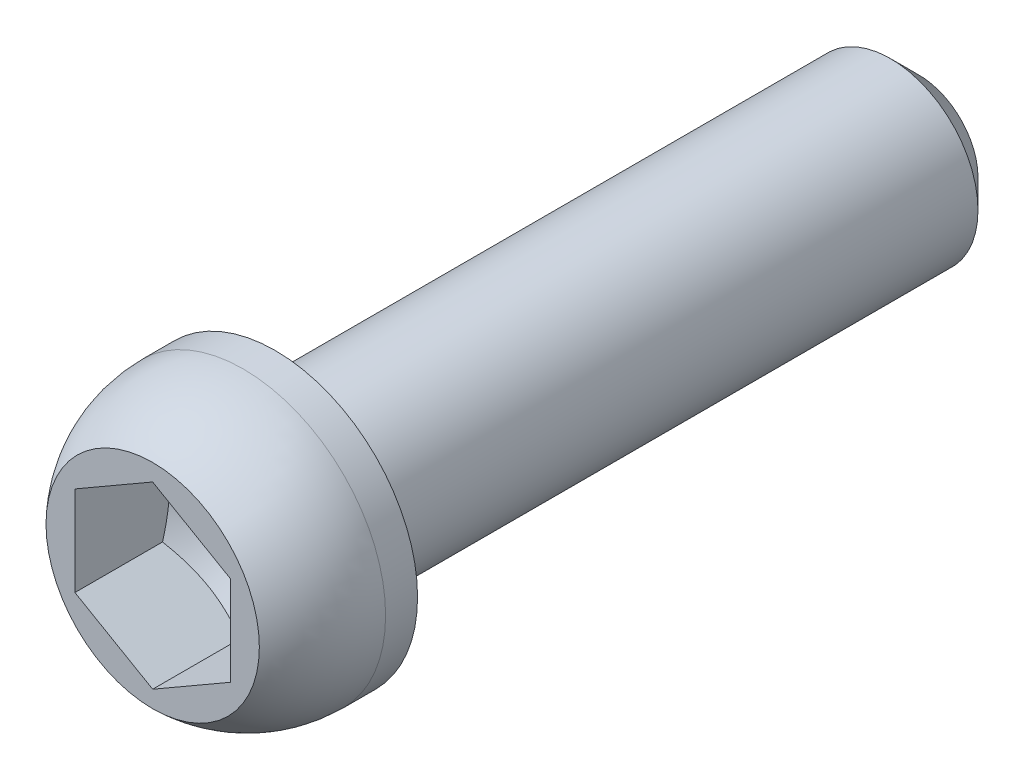
SolidWorks part; units mm, degrees
material "Acier non allié"
ref_plane "Plan de face" through (0, 0, 0) normal (0, 0, 1) x (1, 0, 0)
ref_plane "Plan de dessus" through (0, 0, 0) normal (0, 1, 0) x (1, 0, 0)
ref_plane "Plan de droite" through (0, 0, 0) normal (1, 0, 0) x (0, 0, -1)
other "M4xLxX"
sketch "Esquisse1" plane through (0, 0, 0) normal (1, 0, 0) x (0, 0, -1)
  line L1 (17.5, 2) -> (2.8, 2)
  line L3 (2.8, 3.25) -> (2.07, 3.25)
  line L4 (0, 2.4364) -> (0, 0)
  line L5 (0, 0) -> (17.5, 0)
  line L6 (17.5, 0) -> (17.5, 2)
  line L7 (2.8, 3.25) -> (2.8, 2)
  line L8 (17.5, 0) -> (35.9048, 0) construction
  arc A1 (2.07, 3.25) -> (0, 2.4364) centre (2.07, 0.21) ccw
  dimension "D4" = 3.04
  dimension "Md" = 4
  dimension "D3" = 6.5
  dimension "D5" = 2.8
  dimension "D6" = 0.73
revolve "Révolution1" add sketch "Esquisse1" angle 360 about L8
cosmetic thread "Représentation de filetage2" parameters "X"=6, "D2"=3.22
chamfer "Chanfrein2" distance 0.65 angle 45 1 edges at (2, 0, -17.5)
sketch "Esquisse3" plane through (0, 0, 0) normal (0, 0, 1) x (1, 0, 0)
  line L1 (0, 2.0496) -> (-1.775, 1.0248)
  line L2 (-1.775, 1.0248) -> (-1.775, -1.0248)
  line L3 (-1.775, -1.0248) -> (0, -2.0496)
  line L4 (0, -2.0496) -> (1.775, -1.0248)
  line L5 (1.775, -1.0248) -> (1.775, 1.0248)
  line L6 (1.775, 1.0248) -> (0, 2.0496)
  circle A0 centre (0, 0) radius 1.775 construction
  circle A1 centre (0, 0) radius 2.4364 construction
  circle A2 centre (0, 0) radius 2.4364
  dimension "D1" = 3.55
sketch "Esquisse2" plane through (0, 0, 0) normal (1, 0, 0) x (0, 0, -1)
  line L0 (0, 0) -> (3.5999, 0) construction
  line L1 (0, 0) -> (0, 2.0496)
  line L2 (0, 2.4364) -> (0, -2.4364) construction
  line L3 (0, 2.0496) -> (2, 2.0496)
  line L4 (2, 2.0496) -> (3.1833, 0)
  line L5 (3.1833, 0) -> (0, 0)
  dimension "D1" = 60
  dimension "D2" = 2
revolve "Enlèvement de matière-Révolution1" cut sketch "Esquisse2" angle 360 about L0
extrude "Boss.-Extru.1" add sketch "Esquisse3" against normal up to next
equation "\"D3@Esquisse1\"=2*3.25"
